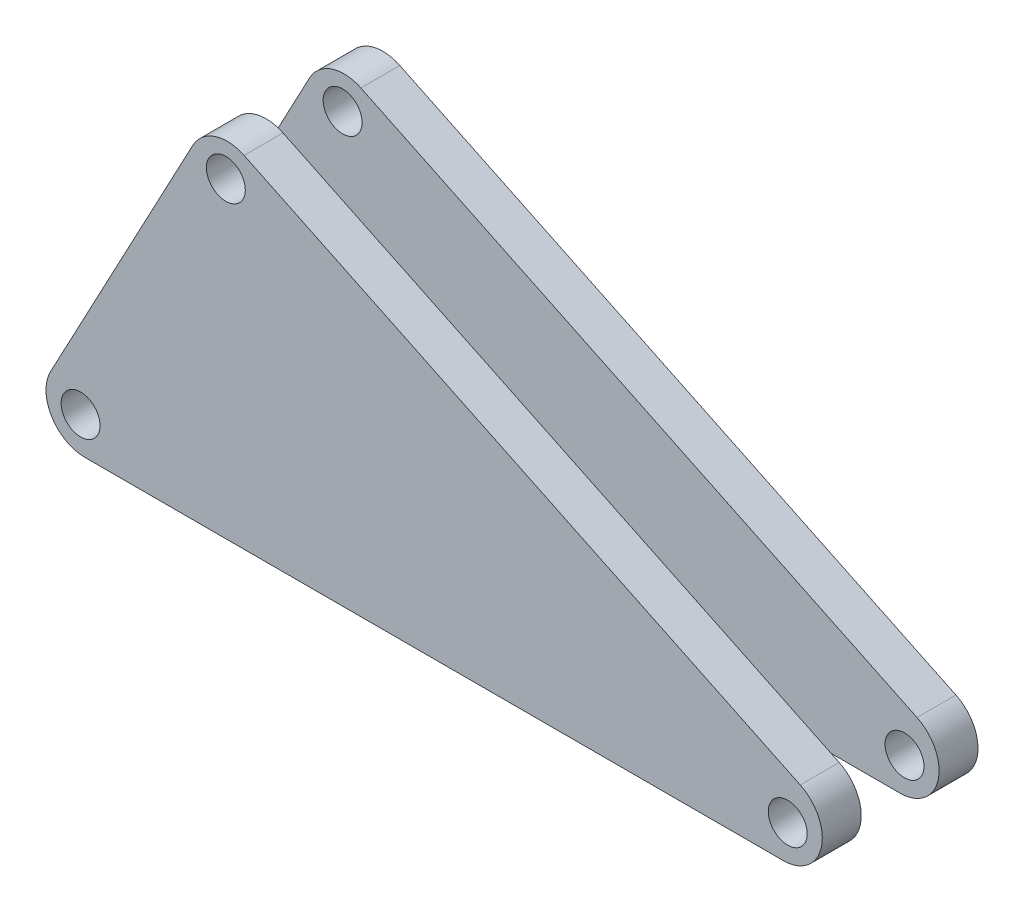
SolidWorks part; units mm, degrees
ref_plane "Front" through (0, 0, 0) normal (0, 0, 1) x (1, 0, 0)
ref_plane "Top" through (0, 0, 0) normal (0, 1, 0) x (1, 0, 0)
ref_plane "Right" through (0, 0, 0) normal (1, 0, 0) x (0, 0, -1)
sketch "Sketch1" plane through (0, 0, 0) normal (0, 0, 1) x (1, 0, 0)
  line L0 (0, 0) -> (-48.9, -91.7867)
  line L1 (-48.9, -91.7867) -> (191.1, -91.7867)
  line L2 (191.1, -91.7867) -> (0, 0)
  dimension "D1" = 104
  dimension "D2" = 212
  dimension "D3" = 240
extrude "Boss-Extrude1" add sketch "Sketch1" along normal blind 40
fillet "Fillet1" radius 10 3 edges at (-48.9, -91.7867, 20) (191.1, -91.7867, 20) (0, 0, 20)
sketch "Sketch2" plane through (0, 0, 40) normal (0, 0, 1) x (1, 0, 0)
  line L0 (-32.2418, -91.7867) -> (147.1829, -91.7867) construction
  line L1 (-4.5097, -8.4647) -> (-41.0674, -77.0847) construction
  circle A0 centre (3.9591, -11.7097) radius 5
  circle A1 centre (-33.3598, -82.7867) radius 5
  circle A2 centre (148.301, -82.7867) radius 5
  arc A3 (-41.0674, -77.0847) -> (-32.2418, -91.7867) centre (-32.2418, -81.7867) ccw construction
  arc A4 (8.6455, -4.1525) -> (-4.5097, -8.4647) centre (4.316, -13.1667) ccw construction
  arc A5 (147.1829, -91.7867) -> (151.5125, -72.7725) centre (147.1829, -81.7867) ccw construction
  dimension "D1" = 10
  dimension "D2" = 1.5
  dimension "D3" = 9
  dimension "D4" = 1.5
  dimension "D5" = 9
  dimension "D6" = 9
  dimension "D7" = 1.5
extrude "Cut-Extrude1" cut sketch "Sketch2" against normal through all
sketch "Sketch3" plane through (0, 0, 0) normal (0, 1, 0) x (1, 0, 0)
  line L0 (151.5125, -40) -> (151.5125, 0) construction
  line L1 (371.1159, -30) -> (-68.0909, -30)
  line L2 (371.1159, -30) -> (371.1159, -10)
  line L3 (371.1159, -10) -> (-68.0909, -10)
  line L4 (-68.0909, -30) -> (-68.0909, -10)
  line L5 (371.1159, -30) -> (-68.0909, -10) construction
  line L6 (371.1159, -10) -> (-68.0909, -30) construction
  point P0 (151.5125, -20)
  dimension "D1" = 20
extrude "Cut-Extrude2" cut sketch "Sketch3" against normal through all
